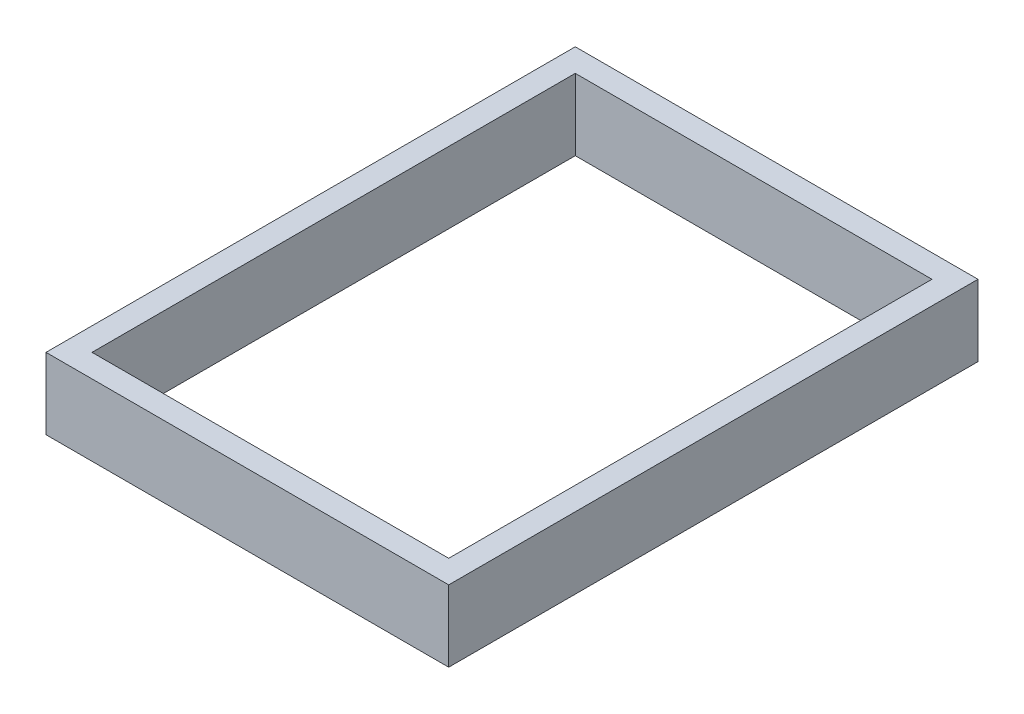
SolidWorks part; units mm, degrees
ref_plane "Front Plane" through (0, 0, 0) normal (0, 0, 1) x (1, 0, 0)
ref_plane "Top Plane" through (0, 0, 0) normal (0, 1, 0) x (1, 0, 0)
ref_plane "Right Plane" through (0, 0, 0) normal (1, 0, 0) x (0, 0, -1)
sketch "Sketch1" plane through (0, 0, 0) normal (0, 1, 0) x (1, 0, 0)
  line L1 (0, 0) -> (20, 0)
  line L2 (0, 0) -> (0, 460)
  line L3 (0, 460) -> (20, 460)
  line L4 (20, 0) -> (20, 460)
  line L5 (20, 460) -> (330, 460)
  line L6 (20, 460) -> (20, 440)
  line L7 (20, 440) -> (330, 440)
  line L8 (330, 460) -> (330, 440)
  line L9 (330, 460) -> (350, 460)
  line L10 (330, 460) -> (330, 0)
  line L11 (330, 0) -> (350, 0)
  line L12 (350, 460) -> (350, 0)
  line L13 (20, 0) -> (330, 0)
  line L14 (20, 0) -> (20, 20)
  line L15 (20, 20) -> (330, 20)
  line L16 (330, 0) -> (330, 20)
  dimension "D1" = 20
  dimension "D2" = 460
  dimension "D3" = 20
  dimension "D4" = 310
  dimension "D5" = 20
  dimension "D6" = 20
extrude "Boss-Extrude1" add sketch "Sketch1" along normal blind 62 contours L15 L4 L13 L10 | L1 L4 L3 L2 | L8 L5 L4 L7 | L12 L9 L8 L10 L11
